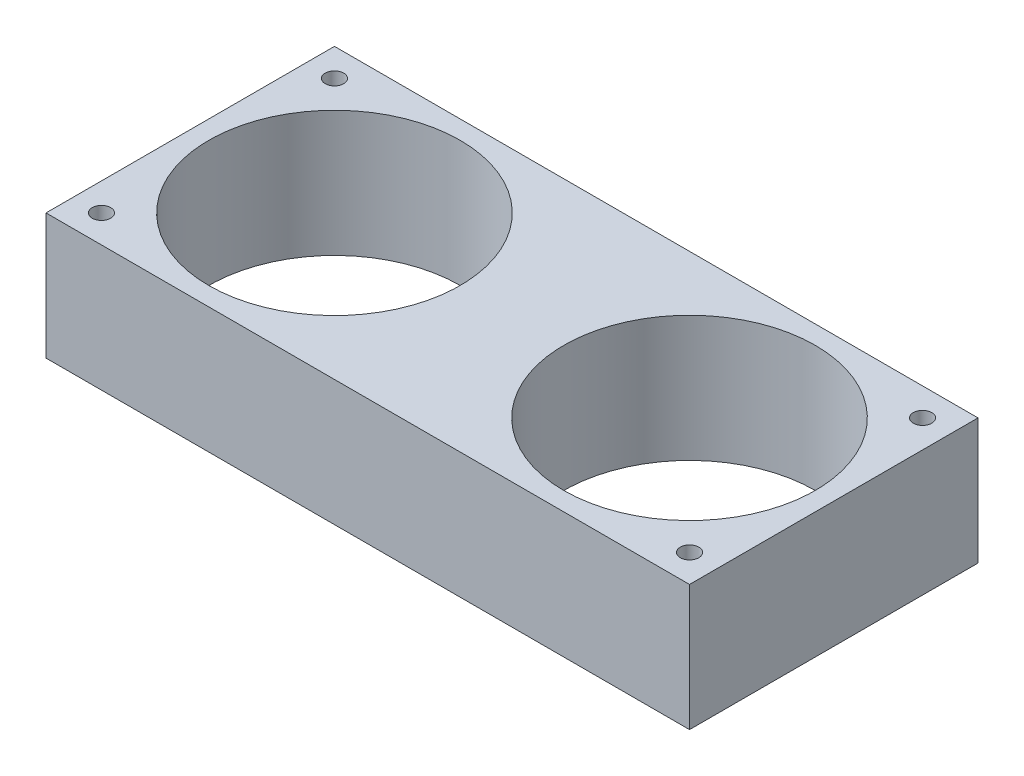
SolidWorks part; units mm, degrees
material "Polyurethane Foam Flexible"
ref_plane "Front Plane" through (0, 0, 0) normal (0, 0, 1) x (1, 0, 0)
ref_plane "Top Plane" through (0, 0, 0) normal (0, 1, 0) x (1, 0, 0)
ref_plane "Right Plane" through (0, 0, 0) normal (1, 0, 0) x (0, 0, -1)
sketch "Sketch1" plane through (0, 0, 0) normal (0, 1, 0) x (1, 0, 0)
  line L0 (-87, -39) -> (87, -39)
  line L1 (-87, -39) -> (-87, 39)
  line L2 (-87, 39) -> (87, 39)
  line L3 (87, -39) -> (87, 39)
  circle A0 centre (48, 0) radius 34
  circle A1 centre (-48, 0) radius 34
  circle A2 centre (-79.5, 31.5) radius 2.5
  circle A3 centre (-79.5, -31.5) radius 2.5
  circle A4 centre (79.5, -31.5) radius 2.5
  circle A5 centre (79.5, 31.5) radius 2.5
extrude "Boss-Extrude1" add sketch "Sketch1" along normal blind 34
